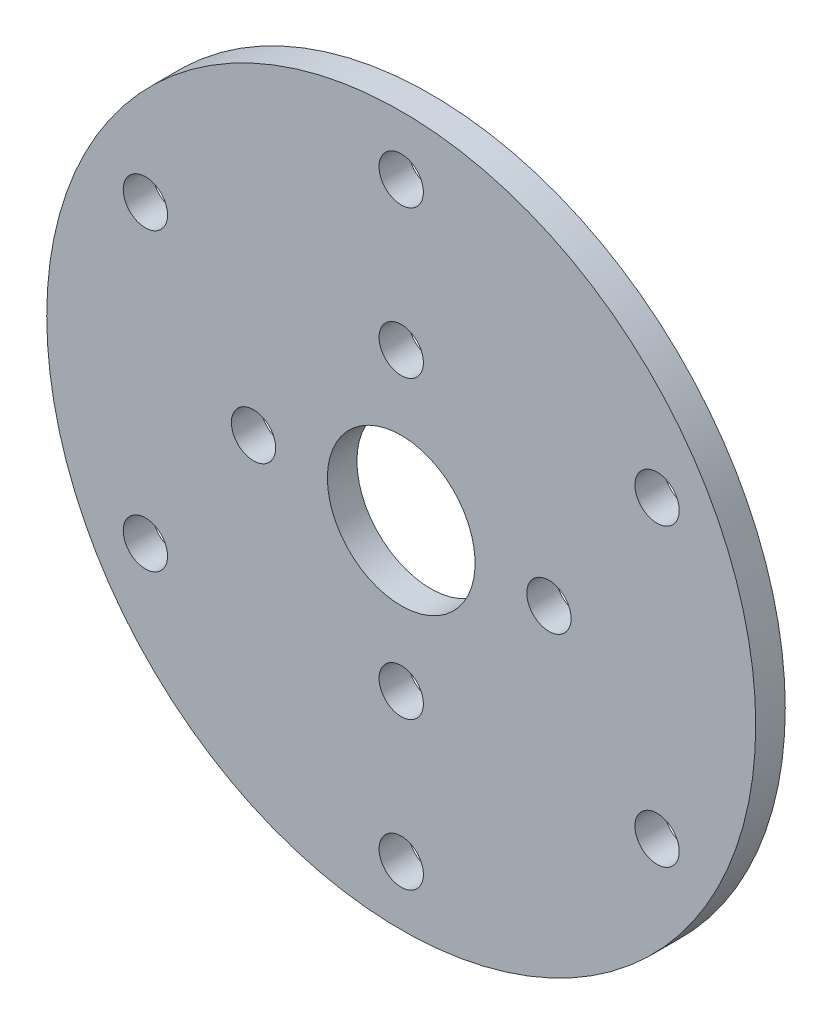
SolidWorks part; units mm, degrees
ref_plane "前视基准面" through (0, 0, 0) normal (0, 0, 1) x (1, 0, 0)
ref_plane "上视基准面" through (0, 0, 0) normal (0, 1, 0) x (1, 0, 0)
ref_plane "右视基准面" through (0, 0, 0) normal (1, 0, 0) x (0, 0, -1)
ref_plane "基准面1" through (0, 0, 2) normal (0, 0, 1) x (1, 0, 0)
sketch "草图1" plane through (0, 0, 2) normal (0, 0, 1) x (1, 0, 0)
  line L0 (10, 0) -> (-10, 0) construction
  line L1 (0, 10) -> (0, -10) construction
  circle A0 centre (-17.3205, 10) radius 1.5
  circle A1 centre (0, -20) radius 1.5
  circle A2 centre (17.3205, 10) radius 1.5
  circle A3 centre (0, 0) radius 5
  circle A4 centre (0, 0) radius 24
  circle A5 centre (0, 20) radius 1.5
  circle A6 centre (17.3205, -10) radius 1.5
  circle A7 centre (-17.3205, -10) radius 1.5
  circle A8 centre (0, 10) radius 1.5
  circle A9 centre (-10, 0) radius 1.5
  circle A10 centre (0, -10) radius 1.5
  circle A11 centre (10, 0) radius 1.5
  dimension "D1" = 20
  dimension "D2" = 20
extrude "凸台-拉伸1" add sketch "草图1" against normal blind 2
